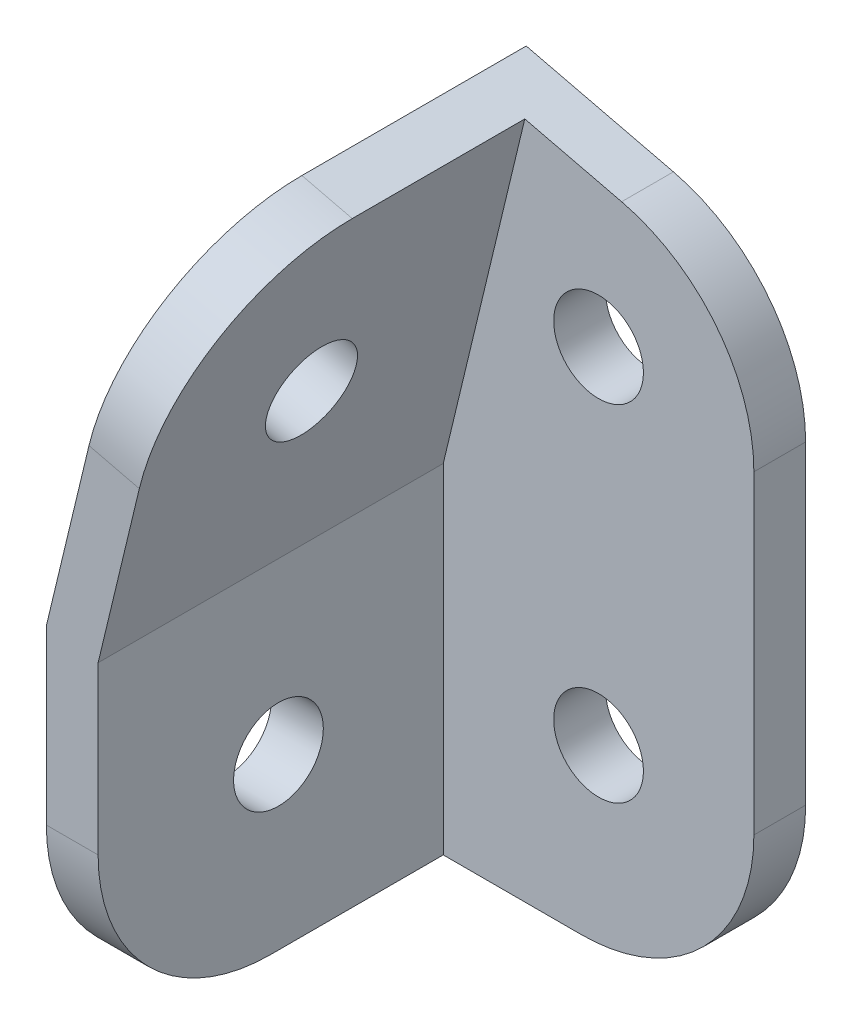
SolidWorks part; units mm, degrees
ref_plane "Plan de face" through (0, 0, 0) normal (0, 0, 1) x (1, 0, 0)
ref_plane "Plan de dessus" through (0, 0, 0) normal (0, 1, 0) x (1, 0, 0)
ref_plane "Plan de droite" through (0, 0, 0) normal (1, 0, 0) x (0, 0, -1)
sketch "Esquisse1" plane through (0, 0, 0) normal (0, 0, 1) x (1, 0, 0)
  line L0 (-100, 325.5) -> (-100, 305.5)
  line L1 (-100, 325.5) -> (-100, 92.65) construction
  line L2 (-100, 305.5) -> (-97, 305.5)
  line L3 (-97, 305.5) -> (-97, 325.1445)
  line L4 (-97, 325.1445) -> (-92.2751, 344.7988)
  line L5 (-92.2751, 344.7988) -> (-95.192, 345.5)
  line L6 (-59.18, 495.3) -> (-100, 325.5) construction
  line L7 (-95.192, 345.5) -> (-100, 325.5)
  dimension "D1" = 20
  dimension "D2" = 20
  dimension "D3" = 3
  dimension "D4" = 3
extrude "Boss.-Extru.1" add sketch "Esquisse1" along normal blind 23
sketch "Esquisse2" plane through (0, 0, 0) normal (0, 0, 1) x (1, 0, 0)
  line L0 (-92.2751, 344.7988) -> (-79, 341.6074)
  line L1 (-79, 341.6074) -> (-79, 305.5)
  line L2 (-79, 305.5) -> (-97, 305.5)
  line L3 (-100, 305.5) -> (-97, 305.5) construction
  line L4 (-92.2751, 344.7988) -> (-95.192, 345.5) construction
  line L5 (-97, 305.5) -> (-97, 325.1445)
  line L6 (-97, 325.1445) -> (-92.2751, 344.7988)
  line L7 (-88, 305.5) -> (-88, 334.9716) construction
  circle A0 centre (-88, 315.5) radius 2.6
  circle A1 centre (-88, 335.5) radius 2.6
  dimension "D2" = 5.2
  dimension "D3" = 5.2
  dimension "D4" = 10
  dimension "D5" = 20
  dimension "D1" = 18
extrude "Boss.-Extru.2" add sketch "Esquisse2" along normal blind 3
sketch "Esquisse3" plane through (-97, 0, 0) normal (1, 0, 0) x (0, 0, -1)
  line L0 (-23, 315.3222) -> (-3, 315.3222) construction
  line L1 (-23, 305.5) -> (-23, 325.1445) construction
  line L2 (-3, 325.1445) -> (-3, 305.5) construction
  circle A0 centre (-12.549, 315.3222) radius 2.6
  dimension "D1" = 5.2
extrude "Enlèv. mat.-Extru.1" cut sketch "Esquisse3" against normal blind 3
sketch "Esquisse4" plane through (-165.5948, 39.8091, 0) normal (0.9723, -0.2337, 0) x (0, 0, -1)
  line L0 (-23, 303.5718) -> (-3, 303.5718) construction
  line L1 (-23, 293.4647) -> (-23, 313.679) construction
  line L2 (-3, 313.679) -> (-3, 293.4647) construction
  circle A0 centre (-13, 303.5718) radius 2.6
  dimension "D1" = 5.2
extrude "Enlèv. mat.-Extru.2" cut sketch "Esquisse4" against normal blind 3
fillet "Congé1" radius 10 4 edges at (-98.5, 305.5, 23) (-93.7335, 345.1494, 23) (-79, 341.6074, 1.5) (-79, 305.5, 1.5)
